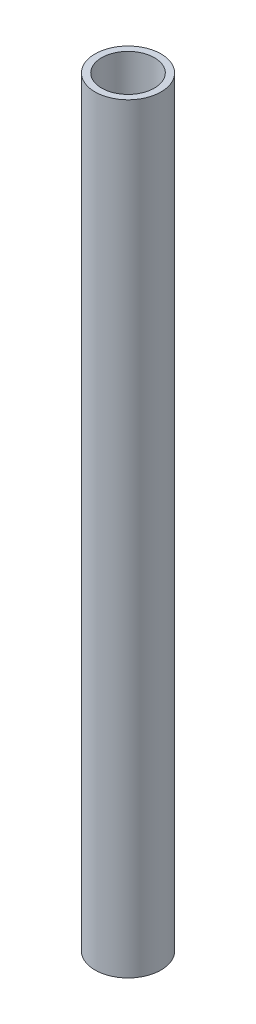
SolidWorks part; units mm, degrees
material "Сталь 08Х21Н5Т ГОСТ 5632-72"
ref_plane "Спереди" through (0, 0, 0) normal (0, 0, 1) x (1, 0, 0)
ref_plane "Сверху" through (0, 0, 0) normal (0, 1, 0) x (1, 0, 0)
ref_plane "Справа" through (0, 0, 0) normal (1, 0, 0) x (0, 0, -1)
other "Configuration Table"
sketch "Эскиз1" plane through (0, 0, 0) normal (0, 1, 0) x (1, 0, 0)
  circle A0 centre (0, 0) radius 4
  circle A1 centre (0, 0) radius 5
  dimension "D1" = 10
  dimension "D2" = 8
extrude "Бобышка-Вытянуть1" add sketch "Эскиз1" along normal blind 115.3
